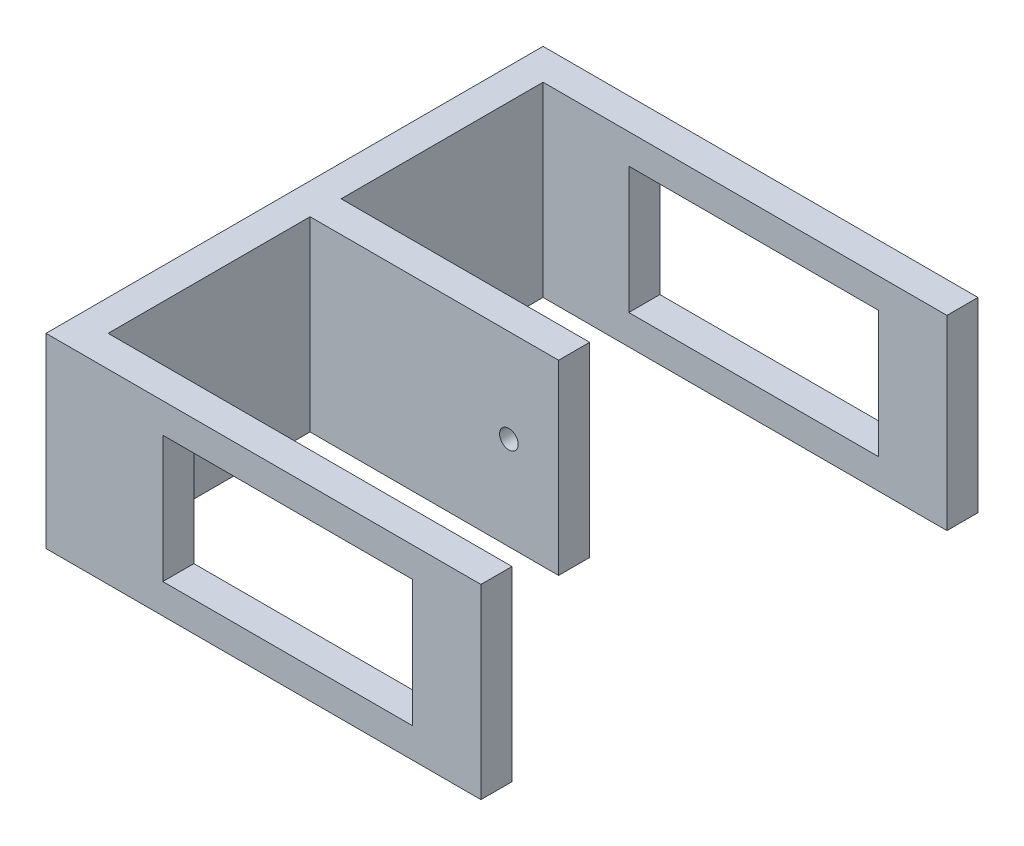
SolidWorks part; units mm, degrees
ref_plane "前视基准面" through (0, 0, 0) normal (0, 0, 1) x (1, 0, 0)
ref_plane "上视基准面" through (0, 0, 0) normal (0, 1, 0) x (1, 0, 0)
ref_plane "右视基准面" through (0, 0, 0) normal (1, 0, 0) x (0, 0, -1)
sketch "草图1" plane through (0, 0, 0) normal (0, 0, 1) x (1, 0, 0)
  line L1 (0, 0) -> (70, 0)
  line L2 (0, 0) -> (0, 30)
  line L3 (0, 30) -> (70, 30)
  line L4 (70, 0) -> (70, 30)
  dimension "D1" = 70
  dimension "D2" = 30
extrude "凸台-拉伸1" add sketch "草图1" along normal blind 5
sketch "草图2" plane through (0, 0, 5) normal (0, 0, 1) x (1, 0, 0)
  line L0 (0, 0) -> (70, 0) construction
  line L1 (0, 30) -> (5, 30)
  line L2 (0, 30) -> (0, 0)
  line L3 (0, 0) -> (5, 0)
  line L4 (5, 30) -> (5, 0)
  dimension "D1" = 5
extrude "凸台-拉伸2" add sketch "草图2" along normal blind 75
sketch "草图3" plane through (5, 0, 0) normal (1, 0, 0) x (0, 0, -1)
  line L0 (-80, 0) -> (-5, 0) construction
  line L1 (-80, 30) -> (-75, 30)
  line L2 (-80, 30) -> (-80, 0)
  line L3 (-80, 0) -> (-75, 0)
  line L4 (-75, 30) -> (-75, 0)
  dimension "D1" = 5
extrude "凸台-拉伸3" add sketch "草图3" along normal blind 65
sketch "草图4" plane through (5, 0, 0) normal (1, 0, 0) x (0, 0, -1)
  line L0 (-40, 30) -> (-40, 0) construction
  line L1 (-75, 30) -> (-5, 30) construction
  line L2 (-75, 0) -> (-5, 0) construction
  line L4 (-42.5, 0) -> (-37.5, 0)
  line L5 (-42.5, 0) -> (-42.5, 30)
  line L6 (-42.5, 30) -> (-37.5, 30)
  line L7 (-37.5, 0) -> (-37.5, 30)
  line L8 (-42.5, 0) -> (-37.5, 30) construction
  line L9 (-42.5, 30) -> (-37.5, 0) construction
  point P7 (-40, 15)
  dimension "D1" = 5
extrude "凸台-拉伸4" add sketch "草图4" along normal blind 40
sketch "草图5" plane through (0, 0, 42.5) normal (0, 0, 1) x (1, 0, 0)
  line L0 (45, 15) -> (10.2679, 15) construction
  line L1 (45, 30) -> (45, 0) construction
  circle A0 centre (37, 15) radius 1.5
  dimension "D1" = 8
  dimension "D2" = 3
sketch "草图6" plane through (0, 0, 0) normal (0, 0, -1) x (-1, 0, 0)
  line L0 (-70, 15) -> (0, 15) construction
  line L1 (-70, 0) -> (-70, 30) construction
  line L2 (0, 30) -> (0, 0) construction
  line L4 (-18.8, 4.8) -> (-59, 4.8)
  line L5 (-18.8, 4.8) -> (-18.8, 25.2)
  line L6 (-18.8, 25.2) -> (-59, 25.2)
  line L7 (-59, 4.8) -> (-59, 25.2)
  line L8 (-18.8, 4.8) -> (-59, 25.2) construction
  line L9 (-18.8, 25.2) -> (-59, 4.8) construction
  point P6 (-38.9, 15)
  dimension "D1" = 40.2
  dimension "D2" = 20.4
  dimension "D3" = 11
extrude "切除-拉伸3" cut sketch "草图6" against normal up to next
sketch "草图7" plane through (0, 0, 80) normal (0, 0, 1) x (1, 0, 0)
  line L0 (0, 15) -> (71.9559, 15) construction
  line L1 (0, 30) -> (0, 0) construction
  line L2 (70, 30) -> (70, 0) construction
  line L3 (59, 4.8) -> (18.8, 4.8)
  line L4 (59, 4.8) -> (59, 25.2)
  line L5 (59, 25.2) -> (18.8, 25.2)
  line L6 (18.8, 4.8) -> (18.8, 25.2)
  line L7 (59, 4.8) -> (18.8, 25.2) construction
  line L8 (59, 25.2) -> (18.8, 4.8) construction
  point P4 (38.9, 15)
  dimension "D1" = 40.2
  dimension "D2" = 20.4
  dimension "D3" = 11
extrude "切除-拉伸4" cut sketch "草图7" against normal up to next
extrude "切除-拉伸5" cut sketch "草图5" against normal up to next
